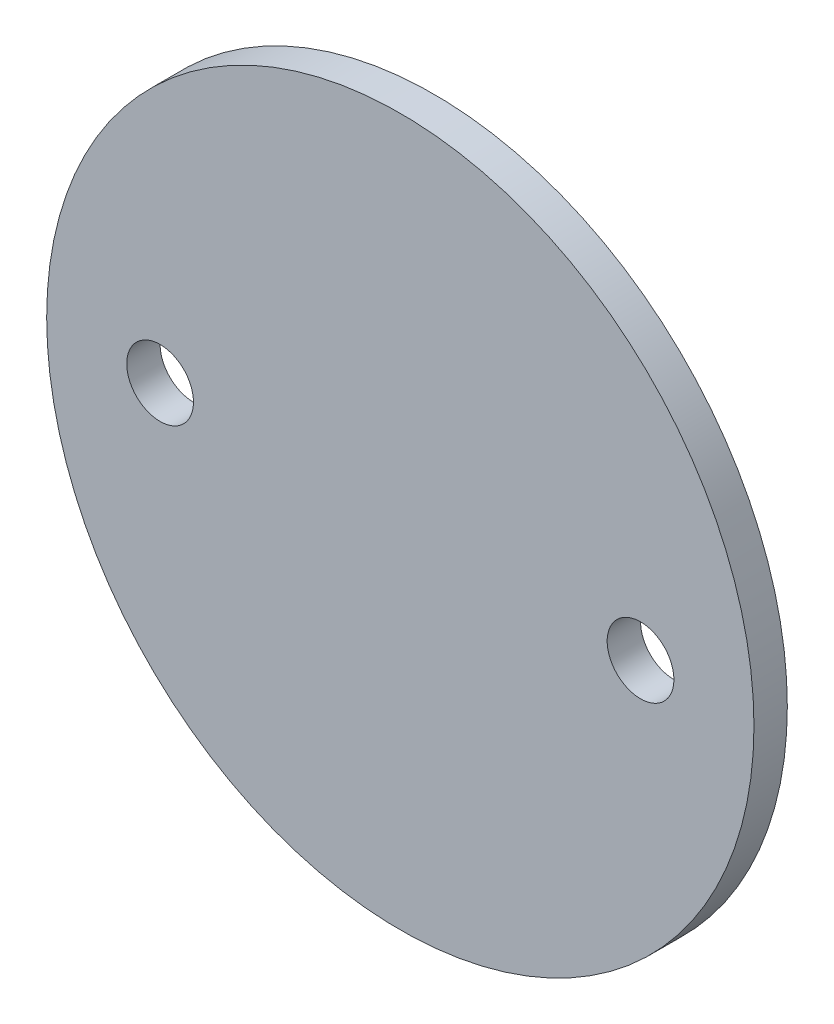
SolidWorks part; units mm, degrees
ref_plane "Front Plane" through (0, 0, 0) normal (0, 0, 1) x (1, 0, 0)
ref_plane "Top Plane" through (0, 0, 0) normal (0, 1, 0) x (1, 0, 0)
ref_plane "Right Plane" through (0, 0, 0) normal (1, 0, 0) x (0, 0, -1)
sketch "Sketch1" plane through (0, 0, 0) normal (0, 0, 1) x (1, 0, 0)
  circle A0 centre (0, 0) radius 26.5
  circle A1 centre (18, 0) radius 2.5
  circle A2 centre (-18, 0) radius 2.5
  dimension "D1" = 53
  dimension "D2" = 5
  dimension "D3" = 5
  dimension "D4" = 18
  dimension "D5" = 18
extrude "Boss-Extrude1" add sketch "Sketch1" along normal blind 2.5
